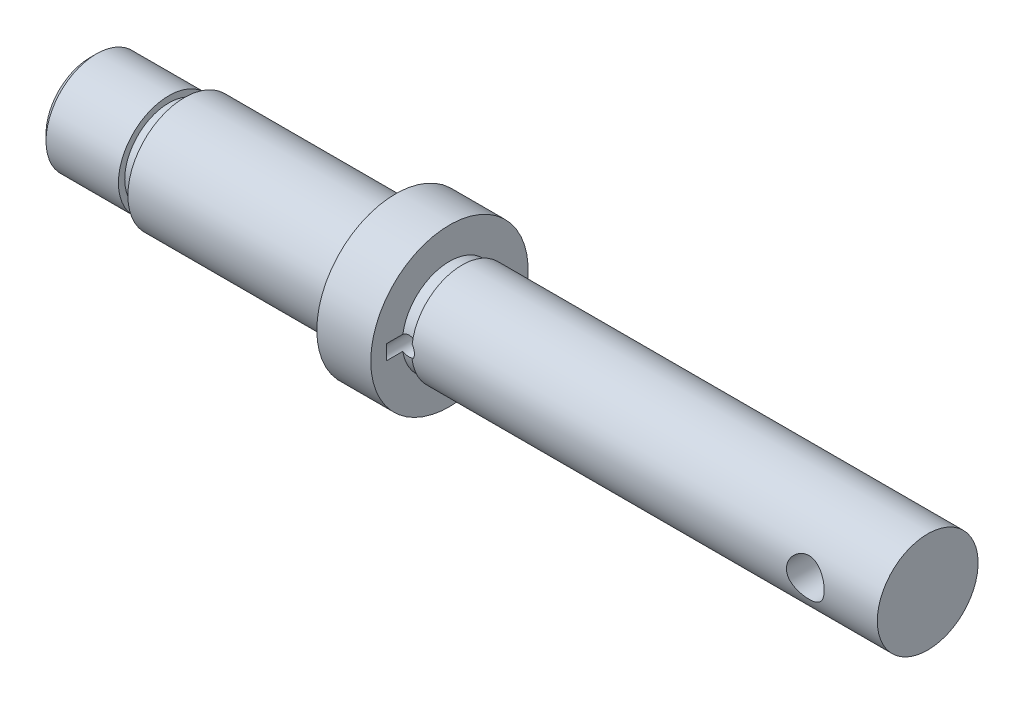
SolidWorks part; units mm, degrees
ref_plane "前视基准面" through (0, 0, 0) normal (0, 0, 1) x (1, 0, 0)
ref_plane "上视基准面" through (0, 0, 0) normal (0, 1, 0) x (1, 0, 0)
ref_plane "右视基准面" through (0, 0, 0) normal (1, 0, 0) x (0, 0, -1)
other "Configuration Table"
sketch "草图1" plane through (0, 0, 0) normal (0, 0, 1) x (1, 0, 0)
  line L0 (0, 0) -> (35848.9557, 0) construction
  line L1 (0, 0) -> (0, 8)
  line L2 (0, 8) -> (-73.9349, 8)
  line L3 (-73.9349, 8) -> (-73.9349, 7.5)
  line L4 (-73.9349, 7.5) -> (-75.9349, 7.5)
  line L5 (-75.9349, 7.5) -> (-75.9349, 12.5)
  line L6 (-75.9349, 12.5) -> (-84.5, 12.5)
  line L7 (-84.5, 12.5) -> (-84.5, 8.5)
  line L8 (-84.5, 8.5) -> (-86.5, 8.5)
  line L9 (-86.5, 8.5) -> (-86.5, 9)
  line L10 (-86.5, 9) -> (-118, 9)
  line L11 (-118, 9) -> (-118, 7)
  line L12 (-118, 7) -> (-120.5, 7)
  line L13 (-120.5, 7) -> (-120.5, 8)
  line L14 (-120.5, 8) -> (-133, 8)
  line L15 (-133, 8) -> (-133, 0)
  line L16 (0, 0) -> (-133, 0)
  dimension "D1" = 133
  dimension "D2" = 16
  dimension "D3" = 25
  dimension "D4" = 18
  dimension "D5" = 16
  dimension "D6" = 48.5
  dimension "D7" = 33.5
  dimension "D8" = 8.5651
  dimension "D9" = 2
  dimension "D10" = 0.5
  dimension "D11" = 2
  dimension "D12" = 0.5
  dimension "D13" = 2.5
  dimension "D14" = 1
revolve "旋转1" add sketch "草图1" angle 360 about L0
cosmetic thread "装饰螺纹线1"
sketch "草图2" plane through (0, 0, 0) normal (0, 0, 1) x (1, 0, 0)
  line L0 (-133, 0) -> (-62.5096, 0) construction
  line L1 (-133, 8) -> (-133, -8) construction
  point P5 (0, 0)
  point P6 (0, 0)
sketch "草图3" plane through (0, 0, 0) normal (0, 0, 1) x (1, 0, 0)
  line L0 (-133, 3.866) -> (-131.5, 3)
  line L1 (-133, 8) -> (-133, -8) construction
  line L2 (-131.5, 3) -> (-125, 3)
  line L3 (-125, 3) -> (-125, 1.5)
  line L4 (-125, 1.5) -> (-75, 1.5)
  line L5 (-133, 0) -> (-62.5096, 0) construction
  line L6 (-133, 0) -> (-73.5, 0)
  line L7 (-133, 3.866) -> (-133, 0)
  arc A0 (-75, 1.5) -> (-73.5, 0) centre (-75, 0) cw
other "对齐组1" parameters "D1"=4.3265, "D2"=1.9402, "D3"=1.5, "D4"=5.7899, "D5"=62.9801, "D6"=1.8545
revolve "切除-旋转3" cut sketch "草图3" angle 360 about L6
sketch "草图4" plane through (0, 0, 0) normal (0, 0, 1) x (1, 0, 0)
  line L0 (-62.5096, 0) -> (1.964, 0) construction
  line L1 (-75.9349, -7.5) -> (-75.9349, 7.5) construction
  circle A0 centre (-11.4349, 0) radius 3
  point P7 (-75.9349, 0)
  dimension "D1" = 6
  dimension "D2" = 64.5
extrude "切除-拉伸1" cut sketch "草图4" against normal through all both and the other way through all
sketch "草图5" plane through (0, 0, 0) normal (0, 0, 1) x (1, 0, 0)
  line L1 (-75, 1.5) -> (-75, -1.5) construction
  circle A1 centre (-75, 0) radius 1.5
  dimension "D1" = 3
extrude "切除-拉伸2" cut sketch "草图5" along normal blind 10
chamfer "倒角1" distance 1 angle 45 1 edges at (-133, 0, 8)
